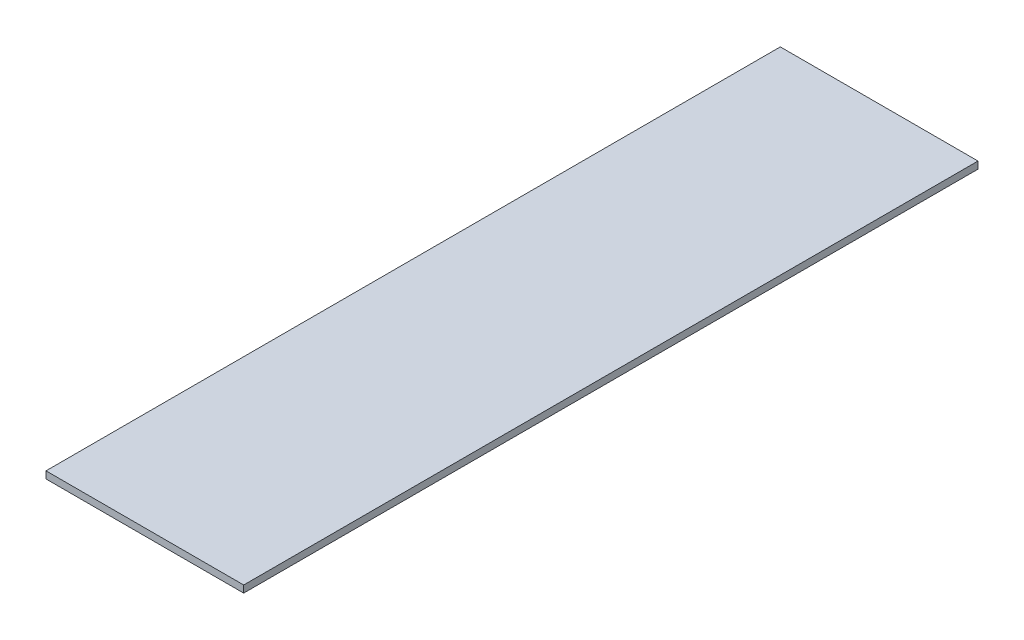
SolidWorks part; units mm, degrees
ref_plane "Front Plane" through (0, 0, 0) normal (0, 0, 1) x (1, 0, 0)
ref_plane "Top Plane" through (0, 0, 0) normal (0, 1, 0) x (1, 0, 0)
ref_plane "Right Plane" through (0, 0, 0) normal (1, 0, 0) x (0, 0, -1)
ref_plane "Plane1"
sketch "Sketch1" plane through (0, 0, 0) normal (0, 1, 0) x (-1, 0, 0)
  line L0 (88.9, 330.2) -> (-88.9, 330.2)
  line L1 (-88.9, 330.2) -> (-88.9, -330.2)
  line L2 (-88.9, -330.2) -> (88.9, -330.2)
  line L3 (88.9, -330.2) -> (88.9, 330.2)
  dimension "D1" = 177.8
  dimension "D2" = 660.4
extrude "Extrusion1" add sketch "Sketch1" along normal blind 6.35
